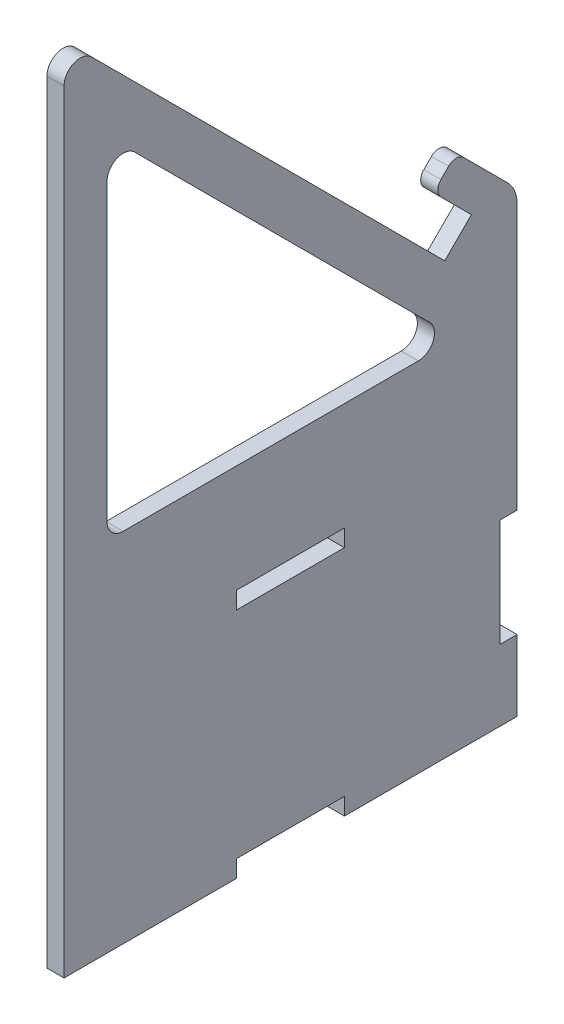
SolidWorks part; units mm, degrees
ref_plane "Plan de face" through (0, 0, 0) normal (0, 0, 1) x (1, 0, 0)
ref_plane "Plan de dessus" through (0, 0, 0) normal (0, 1, 0) x (1, 0, 0)
ref_plane "Plan de droite" through (0, 0, 0) normal (1, 0, 0) x (0, 0, -1)
sketch "Esquisse1" plane through (0, 0, 0) normal (1, 0, 0) x (0, 0, -1)
  line L0 (-42.0729, 0) -> (42.0729, 0)
  line L1 (42.0729, 0) -> (42.0729, 84.9497)
  line L2 (42.0729, 84.9497) -> (30.7591, 96.2635)
  line L3 (30.7591, 96.2635) -> (26.5165, 92.0208)
  line L4 (26.5165, 92.0208) -> (33.5876, 84.9497)
  line L5 (33.5876, 84.9497) -> (28.6378, 80)
  line L6 (28.6378, 80) -> (-42.0729, 150.7107)
  line L7 (-42.0729, 150.7107) -> (-42.0729, 0)
  point P9 (30.052, 88.4853)
  point P12 (0, 0)
  dimension "D1" = 45
  dimension "D2" = 7
  dimension "D3" = 6
  dimension "D4" = 80
  dimension "D5" = 100
  dimension "D6" = 10
extrude "Boss.-Extru.1" add sketch "Esquisse1" along normal blind 3.175
sketch "Esquisse2" plane through (3.175, 0, 0) normal (1, 0, 0) x (0, 0, -1)
  line L0 (-42.0729, 0) -> (42.0729, 0) construction
  line L1 (-10, 0) -> (10, 0)
  line L2 (-10, 0) -> (-10, 3.175)
  line L3 (-10, 3.175) -> (10, 3.175)
  line L4 (10, 0) -> (10, 3.175)
  line L15 (-10, 46.35) -> (10, 46.35)
  line L16 (-10, 46.35) -> (-10, 43.175)
  line L17 (-10, 43.175) -> (10, 43.175)
  line L18 (10, 46.35) -> (10, 43.175)
  line L19 (42.0729, 0) -> (42.0729, 84.9497) construction
  line L29 (42.0729, 33.175) -> (38.8979, 33.175)
  line L30 (42.0729, 33.175) -> (42.0729, 13.175)
  line L31 (42.0729, 13.175) -> (38.8979, 13.175)
  line L32 (38.8979, 33.175) -> (38.8979, 13.175)
  point P6 (0, 0)
  point P22 (38.8979, 23.175)
  dimension "D1" = 20
  dimension "D3" = 3.175
  dimension "D5" = 40
  dimension "D6" = 23.175
extrude "Enlèv. mat.-Extru.1" cut sketch "Esquisse2" against normal through all
fillet "Congé1" radius 6 1 edges at (1.5875, 84.9497, -42.0729)
fillet "Congé2" radius 2 2 edges at (1.5875, 92.0208, -26.5165) (1.5875, 96.2635, -30.7591)
sketch "Esquisse4" plane through (3.175, 0, 0) normal (1, 0, 0) x (0, 0, -1)
  line L0 (30.9741, 66.35) -> (-34.0729, 66.35)
  line L1 (-34.0729, 66.35) -> (-34.0729, 131.397)
  line L2 (-34.0729, 131.397) -> (30.9741, 66.35)
  line L3 (28.6378, 80) -> (-42.0729, 150.7107) construction
  line L4 (-42.0729, 150.7107) -> (-42.0729, 0) construction
  dimension "D1" = 8
  dimension "D2" = 8
  dimension "D3" = 65.047
extrude "Enlèv. mat.-Extru.2" cut sketch "Esquisse4" against normal through all
fillet "Congé4" radius 3 4 edges at (1.5875, 66.35, -30.9741) (1.5875, 66.35, 34.0729) (1.5875, 131.397, 34.0729) (1.5875, 150.7107, 42.0729)
